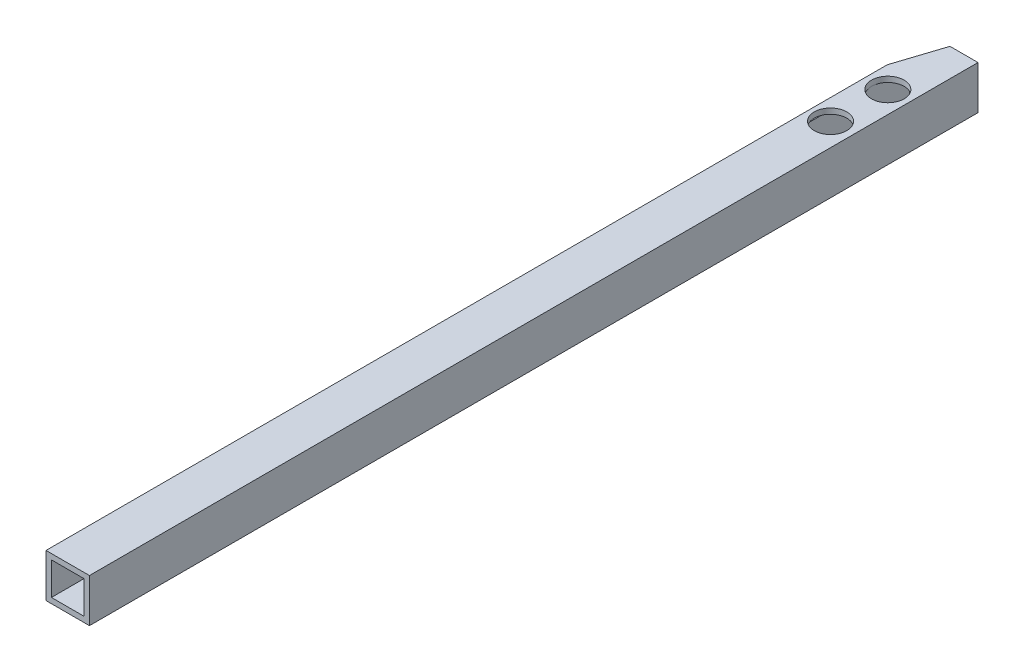
SolidWorks part; units mm, degrees
ref_plane "Front Plane" through (0, 0, 0) normal (0, 0, 1) x (1, 0, 0)
ref_plane "Top Plane" through (0, 0, 0) normal (0, 1, 0) x (1, 0, 0)
ref_plane "Right Plane" through (0, 0, 0) normal (1, 0, 0) x (0, 0, -1)
sketch "Sketch1" plane through (0, 0, 0) normal (0, 0, 1) x (1, 0, 0)
  line L0 (-9.525, 9.525) -> (9.525, 9.525)
  line L2 (-12.7, 12.7) -> (12.7, 12.7)
  line L3 (-12.7, 12.7) -> (-12.7, -12.7)
  line L4 (-12.7, -12.7) -> (12.7, -12.7)
  line L5 (12.7, 12.7) -> (12.7, -12.7)
  line L10 (9.525, 9.525) -> (9.525, -9.525)
  line L11 (-9.525, -9.525) -> (9.525, -9.525)
  line L12 (-9.525, 9.525) -> (-9.525, -9.525)
  point P12 (0, 12.7)
  point P14 (12.7, 0)
  dimension "Wall Thickness" = 3.175
  dimension "Outside Width" = 25.4
  dimension "Outside Height" = 25.4
  dimension "Inside Height" = 19.05
  dimension "Inside Width" = 19.05
sketch "Sketch2" plane through (0, 0, 0) normal (1, 0, 0) x (0, 0, -1)
  line L0 (266.7, 0) -> (-266.7, 0)
  point P4 (0, 0)
  point P7 (-266.7, 0)
  point P10 (266.7, 0)
  dimension "Length" = 533.4
sketch "Sketch3" plane through (0, 0, 0) normal (0, 0, 1) x (1, 0, 0)
  line L21 (12.7, 12.7) -> (-12.7, 12.7)
  line L22 (12.7, -12.7) -> (12.7, 12.7)
  line L23 (-12.7, -12.7) -> (12.7, -12.7)
  line L24 (-12.7, 12.7) -> (-12.7, -12.7)
  line L25 (12.7, 12.7) -> (-12.7, 12.7)
  line L26 (12.7, -12.7) -> (12.7, 12.7)
  line L27 (-12.7, -12.7) -> (12.7, -12.7)
  line L28 (-12.7, 12.7) -> (-12.7, -12.7)
  line L29 (9.525, 9.525) -> (-9.525, 9.525)
  line L30 (9.525, -9.525) -> (9.525, 9.525)
  line L31 (-9.525, -9.525) -> (9.525, -9.525)
  line L32 (-9.525, 9.525) -> (-9.525, -9.525)
  line L33 (9.525, 9.525) -> (-9.525, 9.525)
  line L34 (9.525, -9.525) -> (9.525, 9.525)
  line L35 (-9.525, -9.525) -> (9.525, -9.525)
  line L36 (-9.525, 9.525) -> (-9.525, -9.525)
  dimension "D1" = 0
  dimension "D2" = 0
extrude "Boss-Extrude1" add sketch "Sketch3" along normal up to vertex (266.7 mm away) and the other way up to vertex (266.7 mm away) up to point (0, 0, 266.7) other way up to point (0, 0, -266.7)
sketch "Drawing Reference" plane through (0, 0, 0) normal (1, 0, 0) x (0, 0, -1)
  line L0 (-266.7, 0) -> (266.7, 0) construction
  line L1 (0, -12.7) -> (0, 12.7) construction
  line L2 (-266.7, -12.7) -> (266.7, -12.7) construction
  line L5 (-266.7, 12.7) -> (266.7, 12.7) construction
  point P7 (-248.412, 0)
  point P8 (248.412, 0)
  dimension "D1" = 18.288
sketch "Sketch4" plane through (0, 12.7, 0) normal (0, 1, 0) x (1, 0, 0)
  line L1 (0, 266.7) -> (0, 212.725) construction
  line L7 (-12.7, 225.0135) -> (-12.7, 266.7)
  line L8 (-188.9197, -317.3351) -> (4.6184, 278.3139) construction
  line L10 (-12.7, -266.7) -> (-12.7, 266.7) construction
  line L11 (-12.7, 266.7) -> (12.7, 266.7)
  line L12 (12.7, 266.7) -> (12.7, 252.73)
  line L13 (12.7, -266.7) -> (12.7, 266.7) construction
  line L14 (12.7, 252.73) -> (-3.6943, 252.73)
  line L15 (-3.6943, 252.73) -> (-12.7, 225.0135)
  circle A0 centre (0, 212.725) radius 9.525
  dimension "D1" = 13.97
extrude "Cut-Extrude1" cut sketch "Sketch4" against normal blind 25.4
sketch "Sketch5" plane through (0, 12.7, 0) normal (0, -1, 0) x (1, 0, 0)
  circle A0 centre (-0.6605, -179.8709) radius 9.525
extrude "Cut-Extrude2" cut sketch "Sketch5" along normal blind 3.175
equation "\"D1@Drawing Reference\"=\"Outside Width@Sketch1\" * 0.72"
